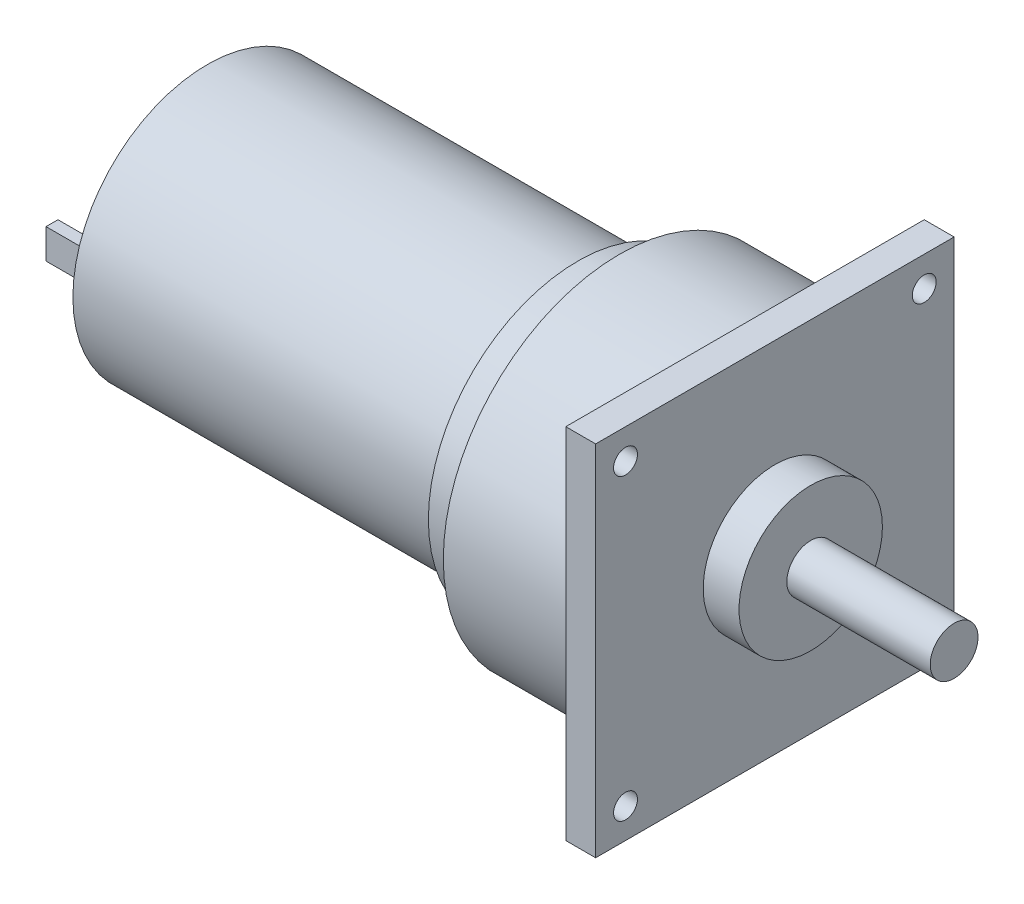
SolidWorks part; units mm, degrees
ref_plane "Front Plane" through (0, 0, 0) normal (0, 0, 1) x (1, 0, 0)
ref_plane "Top Plane" through (0, 0, 0) normal (0, 1, 0) x (1, 0, 0)
ref_plane "Right Plane" through (0, 0, 0) normal (1, 0, 0) x (0, 0, -1)
sketch "Sketch1" plane through (0, 0, 0) normal (1, 0, 0) x (0, 0, -1)
  line L1 (-30, 30) -> (30, 30)
  line L2 (-30, 30) -> (-30, -30)
  line L3 (-30, -30) -> (30, -30)
  line L4 (30, 30) -> (30, -30)
  line L5 (-30, 30) -> (30, -30) construction
  line L6 (-30, -30) -> (30, 30) construction
  point P0 (0, 0)
  dimension "D1" = 60
extrude "Boss-Extrude1" add sketch "Sketch1" along normal blind 5
sketch "Sketch3" plane through (0, 0, 0) normal (-1, 0, 0) x (0, 0, 1)
  circle A0 centre (0, 0) radius 29.5
  dimension "D1" = 59
extrude "Boss-Extrude2" add sketch "Sketch3" along normal blind 21
sketch "Sketch4" plane through (-21, 0, 0) normal (-1, 0, 0) x (0, 0, 1)
  circle A0 centre (0, 0) radius 25
  dimension "D1" = 50
extrude "Boss-Extrude3" add sketch "Sketch4" along normal blind 7
sketch "Sketch5" plane through (-28, 0, 0) normal (-1, 0, 0) x (0, 0, 1)
  circle A0 centre (0, 0) radius 22.5
  dimension "D1" = 45
extrude "Boss-Extrude4" add sketch "Sketch5" along normal blind 62
sketch "Sketch6" plane through (5, 0, 0) normal (1, 0, 0) x (0, 0, -1)
  line L1 (-25, -25) -> (25, -25) construction
  line L2 (-25, -25) -> (-25, 25) construction
  line L3 (-25, 25) -> (25, 25) construction
  line L4 (25, -25) -> (25, 25) construction
  line L5 (-25, -25) -> (25, 25) construction
  line L6 (-25, 25) -> (25, -25) construction
  circle A0 centre (-25, 25) radius 2
  circle A1 centre (25, 25) radius 2
  circle A2 centre (25, -25) radius 2
  circle A3 centre (-25, -25) radius 2
  point P0 (0, 0)
  dimension "D3" = 4
  dimension "D1" = 50
  dimension "D2" = 50
extrude "Cut-Extrude1" cut sketch "Sketch6" against normal up to next
sketch "Sketch7" plane through (5, 0, 0) normal (1, 0, 0) x (0, 0, -1)
  circle A0 centre (0, 0) radius 12
  dimension "D1" = 24
extrude "Boss-Extrude5" add sketch "Sketch7" along normal blind 6
sketch "Sketch8" plane through (11, 0, 0) normal (1, 0, 0) x (0, 0, -1)
  circle A0 centre (0, 0) radius 4
  dimension "D1" = 8
extrude "Boss-Extrude6" add sketch "Sketch8" along normal blind 30 from surface at -6 starting at face at (5, 0, -12)
sketch "Sketch9" plane through (-90, 0, 0) normal (-1, 0, 0) x (0, 0, 1)
  line L0 (-16, 0) -> (16, 0) construction
  line L2 (-17, 2.5) -> (-15, 2.5)
  line L3 (-17, 2.5) -> (-17, -2.5)
  line L4 (-17, -2.5) -> (-15, -2.5)
  line L5 (-15, 2.5) -> (-15, -2.5)
  line L6 (-17, 2.5) -> (-15, -2.5) construction
  line L7 (-17, -2.5) -> (-15, 2.5) construction
  line L8 (15, 2.5) -> (17, 2.5)
  line L9 (15, 2.5) -> (15, -2.5)
  line L10 (15, -2.5) -> (17, -2.5)
  line L11 (17, 2.5) -> (17, -2.5)
  line L12 (15, 2.5) -> (17, -2.5) construction
  line L13 (15, -2.5) -> (17, 2.5) construction
  circle A0 centre (0, 0) radius 2.5
  point P6 (0, 0)
  dimension "D1" = 5
  dimension "D2" = 5
  dimension "D3" = 2
  dimension "D4" = 5
  dimension "D5" = 2
  dimension "D6" = 32
extrude "Boss-Extrude7" add sketch "Sketch9" along normal blind 10
